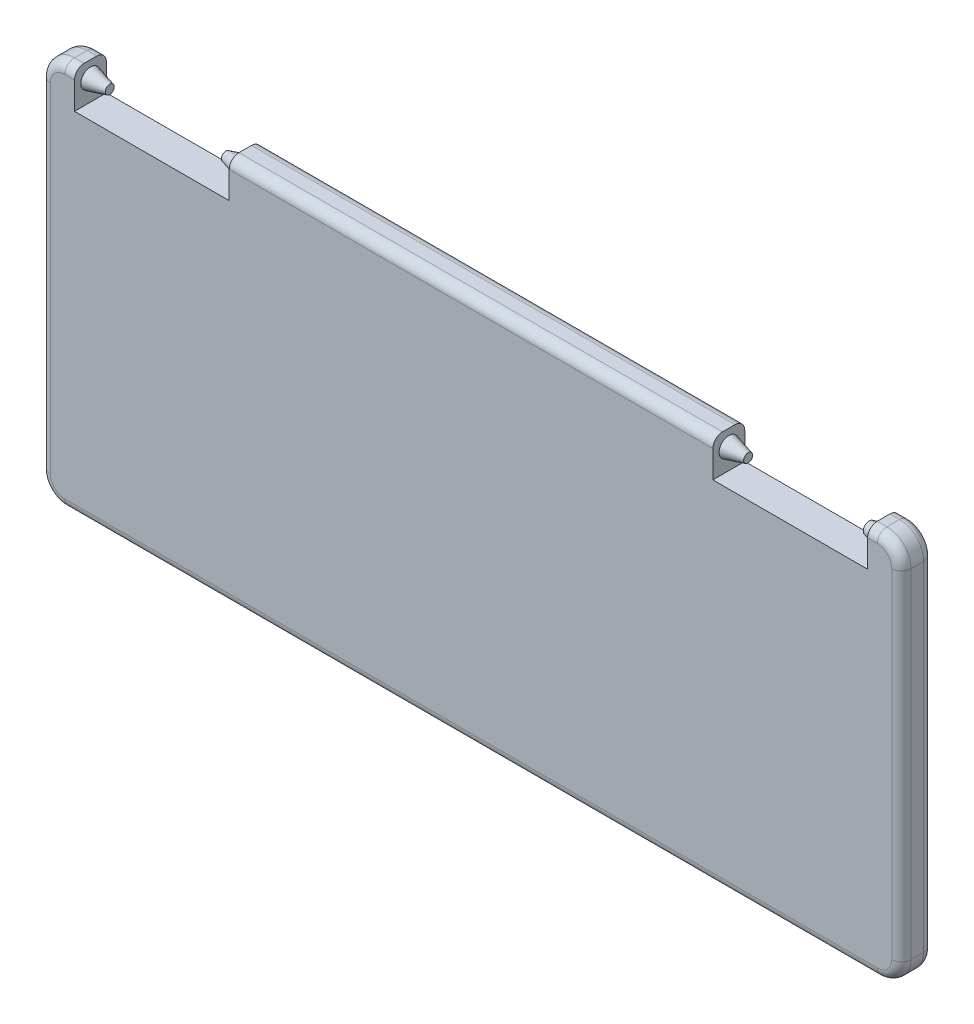
SolidWorks part; units mm, degrees
ref_plane "Front Plane" through (0, 0, 0) normal (0, 0, 1) x (1, 0, 0)
ref_plane "Top Plane" through (0, 0, 0) normal (0, 1, 0) x (1, 0, 0)
ref_plane "Right Plane" through (0, 0, 0) normal (1, 0, 0) x (0, 0, -1)
sketch "Sketch1" plane through (0, 0, 0) normal (0, 0, 1) x (1, 0, 0)
  line L1 (0, 80) -> (178, 80)
  line L2 (0, 80) -> (0, 0)
  line L3 (0, 0) -> (178, 0)
  line L4 (178, 80) -> (178, 0)
  dimension "D1" = 178
  dimension "D2" = 80
extrude "Boss-Extrude1" add sketch "Sketch1" along normal blind 6.6
fillet "Fillet1" radius 5 4 edges at (178, 0, 3.3) (0, 0, 3.3) (178, 80, 3.3) (0, 80, 3.3)
sketch "Sketch5" plane through (0, 0, 6.6) normal (0, 0, 1) x (1, 0, 0)
  line L1 (7, 80) -> (39, 80)
  line L2 (7, 80) -> (7, 72.4)
  line L3 (7, 72.4) -> (39, 72.4)
  line L4 (39, 80) -> (39, 72.4)
  line L6 (178, 5) -> (178, 75) construction
  line L15 (139, 80) -> (171, 80)
  line L16 (139, 80) -> (139, 72.4)
  line L17 (139, 72.4) -> (171, 72.4)
  line L18 (171, 80) -> (171, 72.4)
  line L23 (173, 80) -> (5, 80) construction
  line L24 (0, 75) -> (0, 5) construction
  dimension "D1" = 32
  dimension "D2" = 0
  dimension "D3" = 7.6
  dimension "D4" = 7
  dimension "D5" = 7
extrude "Cut-Extrude1" cut sketch "Sketch5" against normal up to surface (6.6 mm away) up to face at (89, 40, 0)
sketch "Sketch6" plane through (171, 0, 0) normal (-1, 0, 0) x (0, 0, 1)
  line L1 (0, 72.4) -> (0, 80) construction
  line L2 (0, 80) -> (6.6, 80) construction
  circle A0 centre (3.3, 76.7) radius 2
  dimension "D1" = 4
  dimension "D3" = 3.3
  dimension "D2" = 3.3
sketch "Sketch9" plane through (39, 0, 0) normal (-1, 0, 0) x (0, 0, 1)
  line L0 (0, 80) -> (6.6, 80) construction
  line L1 (0, 72.4) -> (0, 80) construction
  circle A0 centre (3.3, 76.7) radius 2
  dimension "D1" = 3.3
  dimension "D2" = 3.3
  dimension "D3" = 4
sketch "Sketch10" plane through (7, 0, 0) normal (1, 0, 0) x (0, 0, -1)
  line L0 (0, 80) -> (-6.6, 80) construction
  line L3 (-6.6, 80) -> (-6.6, 72.4) construction
  circle A0 centre (-3.3, 76.7) radius 2
  dimension "D1" = 4
  dimension "D3" = 3.3
  dimension "D2" = 3.3
sketch "Sketch13" plane through (139, 0, 0) normal (1, 0, 0) x (0, 0, -1)
  line L0 (0, 80) -> (-6.6, 80) construction
  line L3 (-6.6, 80) -> (-6.6, 72.4) construction
  circle A0 centre (-3.3, 76.7) radius 2
  dimension "D1" = 4
  dimension "D3" = 3.3
  dimension "D2" = 3.3
extrude "Boss-Extrude2" add sketch "Sketch13" along normal blind 4 draft 15 contours A0
extrude "Boss-Extrude5" add sketch "Sketch10" along normal blind 4 draft 15 contours A0
extrude "Boss-Extrude6" add sketch "Sketch9" along normal blind 4 draft 15 contours A0
extrude "Boss-Extrude9" add sketch "Sketch6" along normal blind 3 draft 15 contours A0
fillet "Zaoblit4" radius 2 20 edges at (172, 80, 6.6) (89, 80, 6.6) (6, 80, 6.6) (6, 80, 0) (172, 80, 0) (89, 80, 0) (176.5355, 78.5355, 6.6) (178, 40, 6.6) (176.5355, 1.4645, 6.6) (89, 0, 6.6) (1.4645, 1.4645, 6.6) (0, 40, 6.6) (1.4645, 78.5355, 6.6) (1.4645, 78.5355, 0) (0, 40, 0) (1.4645, 1.4645, 0) (89, 0, 0) (176.5355, 1.4645, 0) (178, 40, 0) (176.5355, 78.5355, 0)
